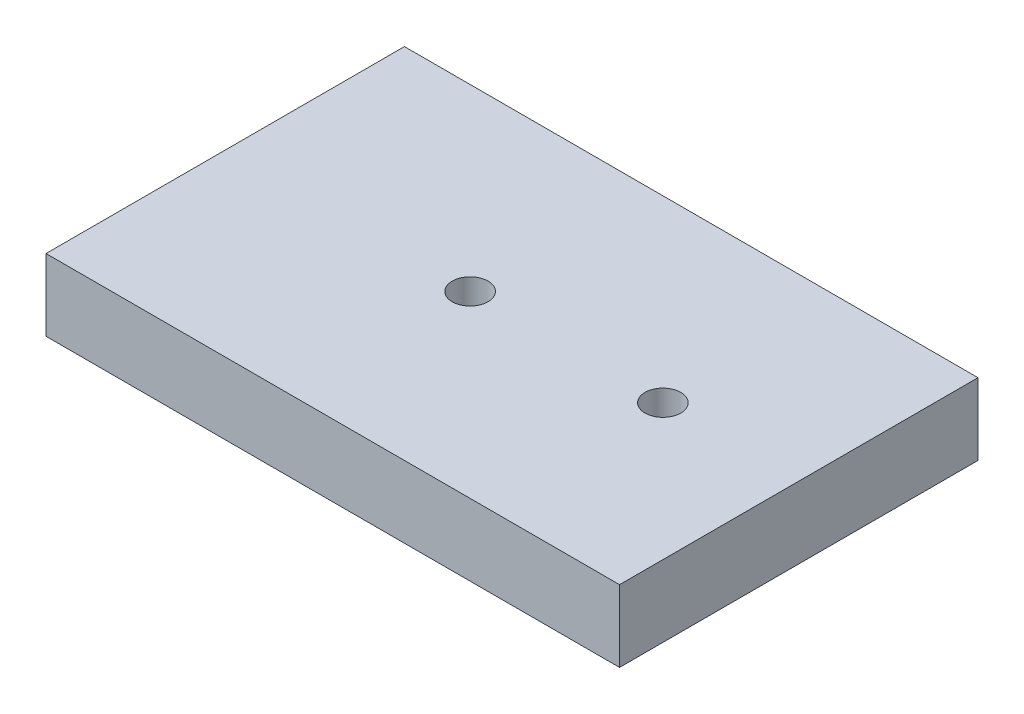
SolidWorks part; units mm, degrees
ref_plane "Front Plane" through (0, 0, 0) normal (0, 0, 1) x (1, 0, 0)
ref_plane "Top Plane" through (0, 0, 0) normal (0, 1, 0) x (1, 0, 0)
ref_plane "Right Plane" through (0, 0, 0) normal (1, 0, 0) x (0, 0, -1)
sketch "Croquis1" plane through (0, 0, 0) normal (0, 1, 0) x (1, 0, 0)
  line L1 (-80, 50) -> (80, 50)
  line L2 (-80, 50) -> (-80, -50)
  line L3 (-80, -50) -> (80, -50)
  line L4 (80, 50) -> (80, -50)
  line L5 (-80, 50) -> (80, -50) construction
  line L6 (-80, -50) -> (80, 50) construction
  point P0 (0, 0)
  dimension "D1" = 160
  dimension "D2" = 100
extrude "Saliente-Extruir1" add sketch "Croquis1" along normal blind 20
sketch "Croquis2" plane through (0, 20, 0) normal (0, 1, 0) x (1, 0, 0)
  line L1 (-80, 0) -> (80, 0) construction
  line L2 (-80, 50) -> (-80, -50) construction
  line L3 (80, -50) -> (80, 50) construction
  circle A5 centre (-11.6856, 0) radius 5
  circle A6 centre (42.0944, 0) radius 5
  point P1 (0, 0)
  point P2 (0, 0)
  dimension "D7" = 10
  dimension "D8" = 10
  dimension "D6" = 53.78
extrude "Cortar-Extruir1" cut sketch "Croquis2" against normal blind 9.8 contours A5 | A6
